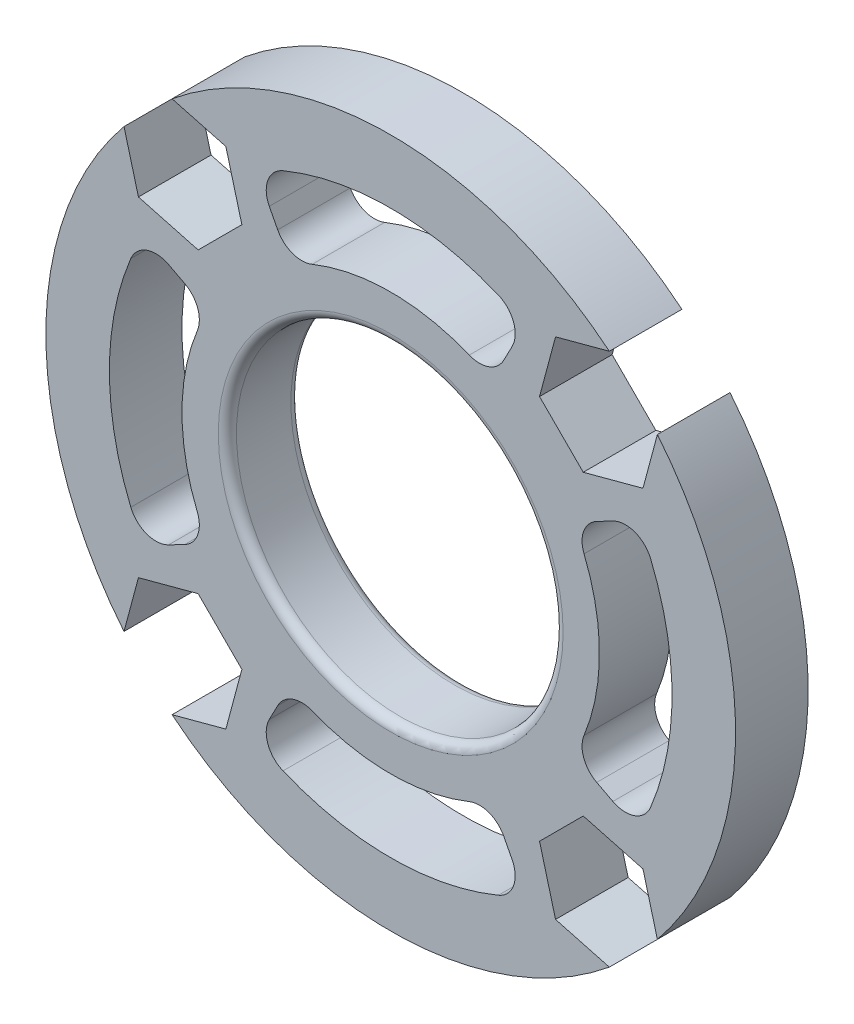
SolidWorks part; units mm, degrees
ref_plane "Front Plane" through (0, 0, 0) normal (0, 0, 1) x (1, 0, 0)
ref_plane "Top Plane" through (0, 0, 0) normal (0, 1, 0) x (1, 0, 0)
ref_plane "Right Plane" through (0, 0, 0) normal (1, 0, 0) x (0, 0, -1)
sketch "Sketch1" plane through (0, 0, 0) normal (0, 0, 1) x (1, 0, 0)
  line L0 (0, 0) -> (0, 19) construction
  line L1 (6.6897, 12.241) -> (6.226, 11.3504)
  line L2 (-6.6897, 12.241) -> (-6.226, 11.3504)
  line L3 (12.241, 6.6897) -> (11.3504, 6.226)
  line L4 (12.241, -6.6897) -> (11.3504, -6.226)
  line L5 (6.6897, -12.241) -> (6.226, -11.3504)
  line L6 (-6.6897, -12.241) -> (-6.226, -11.3504)
  line L7 (-12.241, -6.6897) -> (-11.3504, -6.226)
  line L8 (-12.241, 6.6897) -> (-11.3504, 6.226)
  circle A0 centre (0, 0) radius 19
  circle A1 centre (0, 0) radius 9
  arc A2 (4.3307, 10.6534) -> (-4.3307, 10.6534) centre (0, 0) ccw
  arc A3 (5.9334, 14.3194) -> (-5.9334, 14.3194) centre (0, 0) ccw
  arc A4 (6.6897, 12.241) -> (5.9334, 14.3194) centre (5.3592, 12.9336) ccw
  arc A5 (6.226, 11.3504) -> (4.3307, 10.6534) centre (4.8955, 12.043) cw
  arc A6 (-6.226, 11.3504) -> (-4.3307, 10.6534) centre (-4.8955, 12.043) ccw
  arc A7 (-6.6897, 12.241) -> (-5.9334, 14.3194) centre (-5.3592, 12.9336) cw
  arc A8 (10.6534, -4.3307) -> (10.6534, 4.3307) centre (0, 0) ccw
  arc A9 (11.3504, 6.226) -> (10.6534, 4.3307) centre (12.043, 4.8955) ccw
  arc A10 (12.241, 6.6897) -> (14.3194, 5.9334) centre (12.9336, 5.3592) cw
  arc A11 (14.3194, -5.9334) -> (14.3194, 5.9334) centre (0, 0) ccw
  arc A12 (12.241, -6.6897) -> (14.3194, -5.9334) centre (12.9336, -5.3592) ccw
  arc A13 (11.3504, -6.226) -> (10.6534, -4.3307) centre (12.043, -4.8955) cw
  arc A14 (-4.3307, -10.6534) -> (4.3307, -10.6534) centre (0, 0) ccw
  arc A15 (6.226, -11.3504) -> (4.3307, -10.6534) centre (4.8955, -12.043) ccw
  arc A16 (6.6897, -12.241) -> (5.9334, -14.3194) centre (5.3592, -12.9336) cw
  arc A17 (-5.9334, -14.3194) -> (5.9334, -14.3194) centre (0, 0) ccw
  arc A18 (-6.6897, -12.241) -> (-5.9334, -14.3194) centre (-5.3592, -12.9336) ccw
  arc A19 (-6.226, -11.3504) -> (-4.3307, -10.6534) centre (-4.8955, -12.043) cw
  arc A20 (-10.6534, 4.3307) -> (-10.6534, -4.3307) centre (0, 0) ccw
  arc A21 (-11.3504, -6.226) -> (-10.6534, -4.3307) centre (-12.043, -4.8955) ccw
  arc A22 (-12.241, -6.6897) -> (-14.3194, -5.9334) centre (-12.9336, -5.3592) cw
  arc A23 (-14.3194, 5.9334) -> (-14.3194, -5.9334) centre (0, 0) ccw
  arc A24 (-12.241, 6.6897) -> (-14.3194, 5.9334) centre (-12.9336, 5.3592) ccw
  arc A25 (-11.3504, 6.226) -> (-10.6534, 4.3307) centre (-12.043, 4.8955) cw
  point P56 (0, 0)
  dimension "D1" = 38
  dimension "D2" = 18
  dimension "D3" = 4
  dimension "D4" = 23
  dimension "D5" = 1.5
  dimension "D6" = 55
  dimension "D7" = 4
extrude "Boss-Extrude1" add sketch "Sketch1" along normal blind 4
sketch "Sketch2" plane through (0, 0, 0) normal (0, 0, -1) x (-1, 0, 0)
  line L0 (0, 0) -> (23.1637, 0) construction
  line L2 (19.8581, 19.8581) -> (0, 0) construction
  line L3 (10.6089, -8.2002) -> (8.2002, -10.6089)
  line L4 (13.8992, 9.0818) -> (14.7808, 12.3721)
  line L5 (14.7808, 12.3721) -> (12.3721, 14.7808)
  line L6 (12.3721, 14.7808) -> (9.0818, 13.8992)
  line L7 (9.0818, 13.8992) -> (8.2002, 10.6089)
  line L8 (8.2002, 10.6089) -> (10.6089, 8.2002)
  line L9 (10.6089, 8.2002) -> (13.8992, 9.0818)
  line L10 (8.2002, -10.6089) -> (9.0818, -13.8992)
  line L11 (9.0818, -13.8992) -> (12.3721, -14.7808)
  line L12 (12.3721, -14.7808) -> (14.7808, -12.3721)
  line L13 (14.7808, -12.3721) -> (13.8992, -9.0818)
  line L14 (13.8992, -9.0818) -> (10.6089, -8.2002)
  line L15 (-8.2002, -10.6089) -> (-10.6089, -8.2002)
  line L16 (-10.6089, -8.2002) -> (-13.8992, -9.0818)
  line L17 (-13.8992, -9.0818) -> (-14.7808, -12.3721)
  line L18 (-14.7808, -12.3721) -> (-12.3721, -14.7808)
  line L19 (-12.3721, -14.7808) -> (-9.0818, -13.8992)
  line L20 (-9.0818, -13.8992) -> (-8.2002, -10.6089)
  line L21 (-10.6089, 8.2002) -> (-8.2002, 10.6089)
  line L22 (-8.2002, 10.6089) -> (-9.0818, 13.8992)
  line L23 (-9.0818, 13.8992) -> (-12.3721, 14.7808)
  line L24 (-12.3721, 14.7808) -> (-14.7808, 12.3721)
  line L25 (-14.7808, 12.3721) -> (-13.8992, 9.0818)
  line L26 (-13.8992, 9.0818) -> (-10.6089, 8.2002)
  circle A0 centre (0, 0) radius 16.25 construction
  circle A1 centre (11.4905, 11.4905) radius 2.95 construction
  point P34 (0, 0)
  dimension "D2" = 32.5
  dimension "D1" = 45
  dimension "D3" = 5.9
  dimension "D4" = 4
extrude "Cut-Extrude1" cut sketch "Sketch2" against normal blind 4
fillet "Fillet1" radius 0.5 2 edges at (9, 0, 4) (9, 0, 0)
equation "\"D3@Sketch2\"=5.4+.5"
